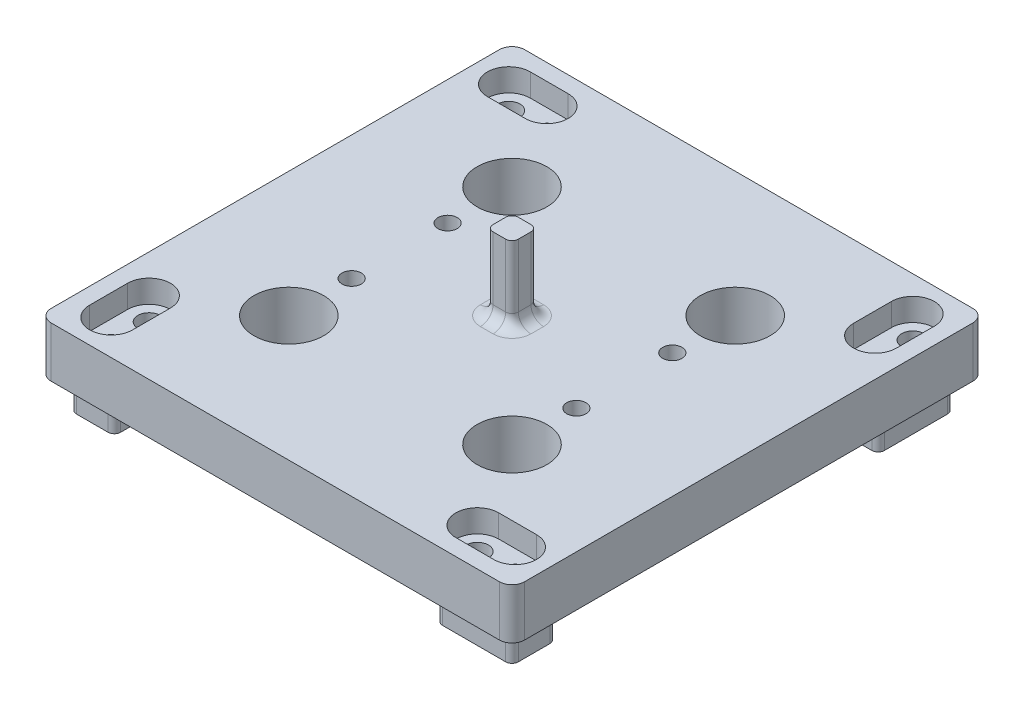
SolidWorks part; units mm, degrees
ref_plane "Front Plane" through (0, 0, 0) normal (0, 0, 1) x (1, 0, 0)
ref_plane "Top Plane" through (0, 0, 0) normal (0, 1, 0) x (1, 0, 0)
ref_plane "Right Plane" through (0, 0, 0) normal (1, 0, 0) x (0, 0, -1)
sketch "Sketch1" plane through (0, 0, 0) normal (0, 1, 0) x (1, 0, 0)
  line L1 (35.5, -37.5) -> (-35.5, -37.5)
  line L2 (37.5, -35.5) -> (37.5, 35.5)
  line L3 (35.5, 37.5) -> (-35.5, 37.5)
  line L4 (-37.5, -35.5) -> (-37.5, 35.5)
  line L5 (37.5, -37.5) -> (-37.5, 37.5) construction
  line L6 (37.5, 37.5) -> (-37.5, -37.5) construction
  arc A0 (35.5, -37.5) -> (37.5, -35.5) centre (35.5, -35.5) ccw
  arc A1 (-35.5, -37.5) -> (-37.5, -35.5) centre (-35.5, -35.5) cw
  arc A2 (37.5, 35.5) -> (35.5, 37.5) centre (35.5, 35.5) ccw
  arc A3 (-35.5, 37.5) -> (-37.5, 35.5) centre (-35.5, 35.5) ccw
  point P0 (0, 0)
  dimension "D3" = 2
  dimension "D1" = 75
  dimension "D2" = 75
extrude "Boss-Extrude1" add sketch "Sketch1" along normal blind 8
sketch "Sketch2" plane through (0, 8, 0) normal (0, 1, 0) x (1, 0, 0)
  line L0 (-31.5, -26) -> (-31.5, -32) construction
  line L2 (35, -35) -> (35, 35) construction
  line L3 (35, 35) -> (-35, 35) construction
  line L5 (35, -35) -> (-35, 35) construction
  line L6 (35, 35) -> (-35, -35) construction
  line L15 (-35, -35) -> (-28, -35)
  line L16 (-35, -35) -> (-35, -23)
  line L17 (-35, -23) -> (-28, -23)
  line L18 (-28, -35) -> (-28, -23)
  line L23 (26, -31.5) -> (32, -31.5) construction
  line L24 (35, -35) -> (23, -35)
  line L25 (35, -35) -> (35, -28)
  line L26 (35, -28) -> (23, -28)
  line L27 (23, -35) -> (23, -28)
  line L28 (-35, 35) -> (-35, -35) construction
  line L29 (35, -35) -> (-35, -35) construction
  line L30 (35, 35) -> (28, 35)
  line L31 (35, 35) -> (35, 23)
  line L32 (35, 23) -> (28, 23)
  line L33 (28, 35) -> (28, 23)
  line L34 (-35, 35) -> (-23, 35)
  line L35 (-35, 35) -> (-35, 28)
  line L36 (-35, 28) -> (-23, 28)
  line L37 (-23, 35) -> (-23, 28)
  line L38 (31.5, 26) -> (31.5, 32) construction
  line L39 (-26, 31.5) -> (-32, 31.5) construction
  circle A0 centre (-31.5, -26) radius 1.775
  circle A1 centre (-31.5, -32) radius 1.775
  circle A4 centre (26, -31.5) radius 1.775
  circle A5 centre (32, -31.5) radius 1.775
  circle A6 centre (31.5, 26) radius 1.775
  circle A7 centre (31.5, 32) radius 1.775
  circle A8 centre (-26, 31.5) radius 1.775
  circle A9 centre (-32, 31.5) radius 1.775
  point P0 (0, 0)
  point P14 (-31.5, -23)
  point P22 (29, -31.5)
  point P23 (29, -28)
  point P29 (35, -31.5)
  point P42 (0, 0)
  dimension "D8" = 3.55
  dimension "D12" = 3.55
  dimension "D1" = 70
  dimension "D2" = 70
  dimension "D3" = 7
  dimension "D4" = 12
  dimension "D5" = 6
  dimension "D6" = 3
  dimension "D7" = 3
  dimension "D9" = 12
  dimension "D10" = 7
  dimension "D11" = 6
  dimension "D13" = 3.5
  dimension "D14" = 3
  dimension "D15" = 2
extrude "Boss-Extrude2" add sketch "Sketch2" against normal blind 13
sketch "Sketch7" plane through (0, 8, 0) normal (0, 1, 0) x (1, 0, 0)
  circle A0 centre (32, -31.5) radius 1.775 construction
  circle A1 centre (26, -31.5) radius 1.775 construction
  circle A2 centre (-31.5, -32) radius 1.775 construction
  circle A3 centre (-31.5, -26) radius 1.775 construction
  circle A4 centre (31.5, 26) radius 1.775 construction
  circle A5 centre (31.5, 32) radius 1.775 construction
  circle A6 centre (-26, 31.5) radius 1.775 construction
  circle A7 centre (-32, 31.5) radius 1.775 construction
  circle A8 centre (32, -31.5) radius 1.775
  circle A9 centre (26, -31.5) radius 1.775
  circle A10 centre (-31.5, -32) radius 1.775
  circle A11 centre (-31.5, -26) radius 1.775
  circle A12 centre (31.5, 26) radius 1.775
  circle A13 centre (31.5, 32) radius 1.775
  circle A14 centre (-26, 31.5) radius 1.775
  circle A15 centre (-32, 31.5) radius 1.775
extrude "Cut-Extrude1" cut sketch "Sketch7" against normal through all
sketch "Sketch8" plane through (0, 0, 0) normal (0, -1, 0) x (1, 0, 0)
  line L0 (-31.5, 32) -> (-31.5, 26) construction
  line L1 (-28.1, 32) -> (-28.1, 26)
  line L2 (-34.9, 32) -> (-34.9, 26)
  line L3 (-32, -31.5) -> (-26, -31.5) construction
  line L4 (-32, -28.1) -> (-26, -28.1)
  line L5 (-32, -34.9) -> (-26, -34.9)
  line L6 (26, 31.5) -> (32, 31.5) construction
  line L7 (26, 34.9) -> (32, 34.9)
  line L8 (26, 28.1) -> (32, 28.1)
  line L9 (31.5, -26) -> (31.5, -32) construction
  line L10 (34.9, -26) -> (34.9, -32)
  line L11 (28.1, -26) -> (28.1, -32)
  arc A0 (-28.1, 32) -> (-34.9, 32) centre (-31.5, 32) ccw
  arc A1 (-34.9, 26) -> (-28.1, 26) centre (-31.5, 26) ccw
  arc A2 (-32, -28.1) -> (-32, -34.9) centre (-32, -31.5) ccw
  arc A3 (-26, -34.9) -> (-26, -28.1) centre (-26, -31.5) ccw
  arc A4 (26, 34.9) -> (26, 28.1) centre (26, 31.5) ccw
  arc A5 (32, 28.1) -> (32, 34.9) centre (32, 31.5) ccw
  arc A6 (34.9, -26) -> (28.1, -26) centre (31.5, -26) ccw
  arc A7 (28.1, -32) -> (34.9, -32) centre (31.5, -32) ccw
  point P4 (-31.5, 29)
  point P9 (-29, -31.5)
  point P22 (29, 31.5)
  point P27 (31.5, -29)
  dimension "D1" = 3.4
  dimension "D2" = 3.4
  dimension "D3" = 3.4
  dimension "D4" = 3.4
fillet "Fillet1" radius 1 16 edges at (-35, -2.5, 23) (35, -2.5, 28) (23, -2.5, 28) (35, -2.5, 35) (23, -2.5, 35) (-28, -2.5, 23) (-35, -2.5, 35) (-28, -2.5, 35) (35, -2.5, -35) (28, -2.5, -35) (28, -2.5, -23) (35, -2.5, -23) (-23, -2.5, -35) (-35, -2.5, -28) (-23, -2.5, -28) (-35, -2.5, -35)
sketch "Sketch9" plane through (0, 8, 0) normal (0, 1, 0) x (1, 0, 0)
  line L1 (17.8, -7.6) -> (-17.8, -7.6) construction
  line L2 (17.8, -7.6) -> (17.8, 7.6) construction
  line L3 (17.8, 7.6) -> (-17.8, 7.6) construction
  line L4 (-17.8, -7.6) -> (-17.8, 7.6) construction
  line L5 (17.8, -7.6) -> (-17.8, 7.6) construction
  line L6 (17.8, 7.6) -> (-17.8, -7.6) construction
  circle A0 centre (-17.8, 7.6) radius 1.525
  circle A1 centre (17.8, 7.6) radius 1.525
  circle A2 centre (-17.8, -7.6) radius 1.525
  circle A3 centre (17.8, -7.6) radius 1.525
  point P0 (0, 0)
  dimension "D3" = 3.05
  dimension "D1" = 35.6
  dimension "D2" = 15.2
extrude "Cut-Extrude3" cut sketch "Sketch9" against normal through all
sketch "Sketch11" plane through (0, 8, 0) normal (0, 1, 0) x (1, 0, 0)
  line L0 (-32, 31.5) -> (-26, 31.5) construction
  line L1 (-32, 34.9) -> (-26, 34.9)
  line L2 (-32, 28.1) -> (-26, 28.1)
  line L3 (-31.5, -26) -> (-31.5, -32) construction
  line L4 (-28.1, -26) -> (-28.1, -32)
  line L5 (-34.9, -26) -> (-34.9, -32)
  line L6 (26, -31.5) -> (32, -31.5) construction
  line L7 (26, -28.1) -> (32, -28.1)
  line L8 (26, -34.9) -> (32, -34.9)
  line L9 (31.5, 32) -> (31.5, 26) construction
  line L10 (34.9, 32) -> (34.9, 26)
  line L11 (28.1, 32) -> (28.1, 26)
  arc A0 (-32, 34.9) -> (-32, 28.1) centre (-32, 31.5) ccw
  arc A1 (-26, 28.1) -> (-26, 34.9) centre (-26, 31.5) ccw
  arc A2 (-28.1, -26) -> (-34.9, -26) centre (-31.5, -26) ccw
  arc A3 (-34.9, -32) -> (-28.1, -32) centre (-31.5, -32) ccw
  arc A4 (26, -28.1) -> (26, -34.9) centre (26, -31.5) ccw
  arc A5 (32, -34.9) -> (32, -28.1) centre (32, -31.5) ccw
  arc A6 (34.9, 32) -> (28.1, 32) centre (31.5, 32) ccw
  arc A7 (28.1, 26) -> (34.9, 26) centre (31.5, 26) ccw
  point P4 (-29, 31.5)
  point P9 (-31.5, -29)
  point P18 (29, -31.5)
  point P27 (31.5, 29)
  dimension "D1" = 3.4
extrude "Cut-Extrude4" cut sketch "Sketch11" against normal blind 3.6
sketch "Sketch12" plane through (0, 8, 0) normal (0, 1, 0) x (1, 0, 0)
  line L1 (17.68, -17.68) -> (-17.68, -17.68) construction
  line L2 (17.68, -17.68) -> (17.68, 17.68) construction
  line L3 (17.68, 17.68) -> (-17.68, 17.68) construction
  line L4 (-17.68, -17.68) -> (-17.68, 17.68) construction
  line L5 (17.68, -17.68) -> (-17.68, 17.68) construction
  line L6 (17.68, 17.68) -> (-17.68, -17.68) construction
  circle A0 centre (-17.68, 17.68) radius 5.525
  circle A1 centre (-17.68, -17.68) radius 5.525
  circle A2 centre (17.68, -17.68) radius 5.525
  circle A3 centre (17.68, 17.68) radius 5.525
  point P0 (0, 0)
  dimension "D3" = 11.05
  dimension "D1" = 35.36
  dimension "D2" = 35.36
extrude "Cut-Extrude5" cut sketch "Sketch12" against normal through all
sketch "Sketch13" plane through (0, 8, 0) normal (0, 1, 0) x (1, 0, 0)
  line L1 (1, -2) -> (-1, -2)
  line L2 (2, -1) -> (2, 1)
  line L3 (1, 2) -> (-1, 2)
  line L4 (-2, -1) -> (-2, 1)
  line L5 (2, -2) -> (-2, 2) construction
  line L6 (2, 2) -> (-2, -2) construction
  arc A0 (-1, -2) -> (-2, -1) centre (-1, -1) cw
  arc A1 (1, -2) -> (2, -1) centre (1, -1) ccw
  arc A2 (2, 1) -> (1, 2) centre (1, 1) ccw
  arc A3 (-1, 2) -> (-2, 1) centre (-1, 1) ccw
  point P0 (0, 0)
  dimension "D3" = 1
  dimension "D1" = 4
  dimension "D2" = 4
extrude "Boss-Extrude3" add sketch "Sketch13" along normal blind 12
fillet "Fillet2" radius 2 8 edges at (-1.7071, 8, 1.7071) (-2, 8, 0) (-1.7071, 8, -1.7071) (0, 8, -2) (1.7071, 8, -1.7071) (2, 8, 0) (1.7071, 8, 1.7071) (0, 8, 2)
equation "\"D9@Sketch2\"=\"D4@Sketch2\""
equation "\"D10@Sketch2\"=\"D3@Sketch2\""
equation "\"D12@Sketch2\"=\"D8@Sketch2\""
equation "\"D14@Sketch2\"=\"D6@Sketch2\""
equation "\"D11@Sketch2\"=\"D5@Sketch2\""
equation "\"D2@Sketch8\"=\"D1@Sketch8\""
equation "\"D3@Sketch8\"=\"D1@Sketch8\""
equation "\"D4@Sketch8\"=\"D1@Sketch8\""
